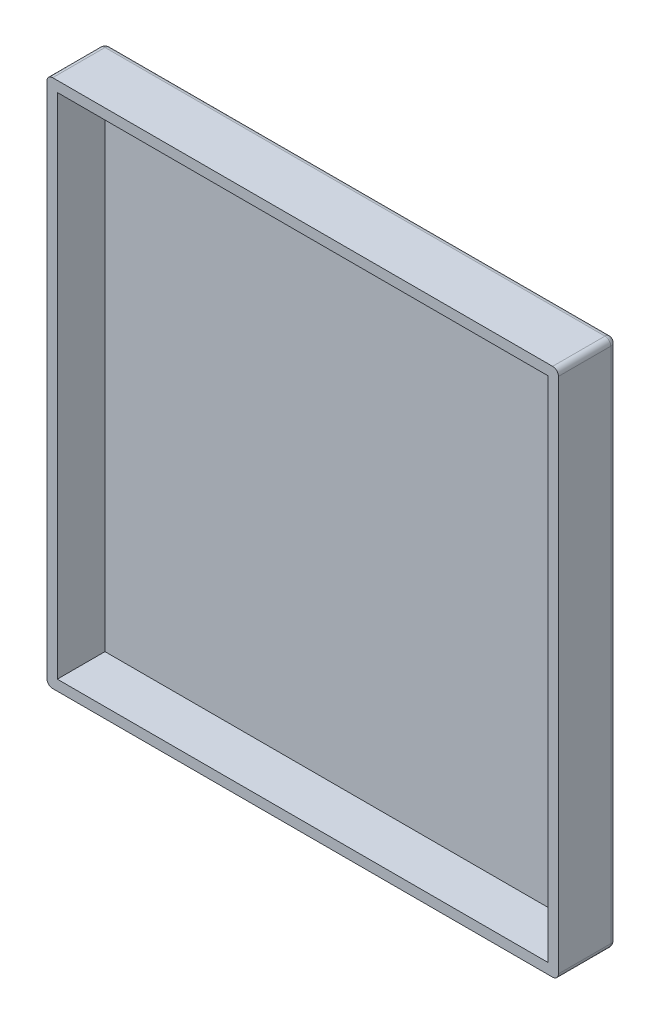
SolidWorks part; units mm, degrees
ref_plane "Front Plane" through (0, 0, 0) normal (0, 0, 1) x (1, 0, 0)
ref_plane "Top Plane" through (0, 0, 0) normal (0, 1, 0) x (1, 0, 0)
ref_plane "Right Plane" through (0, 0, 0) normal (1, 0, 0) x (0, 0, -1)
sketch "Sketch for main shape" plane through (0, 0, 0) normal (0, 0, 1) x (1, 0, 0)
  line L1 (0, 0) -> (88, 0)
  line L2 (0, 0) -> (0, 91)
  line L3 (0, 91) -> (88, 91)
  line L4 (88, 0) -> (88, 91)
  dimension "D1" = 91
  dimension "D2" = 88
extrude "Main shape" add sketch "Sketch for main shape" along normal blind 10
shell "Hollow" thickness 1.8
fillet "Fillets" radius 1 8 edges at (44, 0, 0) (88, 45.5, 0) (44, 91, 0) (0, 45.5, 0) (0, 91, 5) (0, 0, 5) (88, 0, 5) (88, 91, 5)
